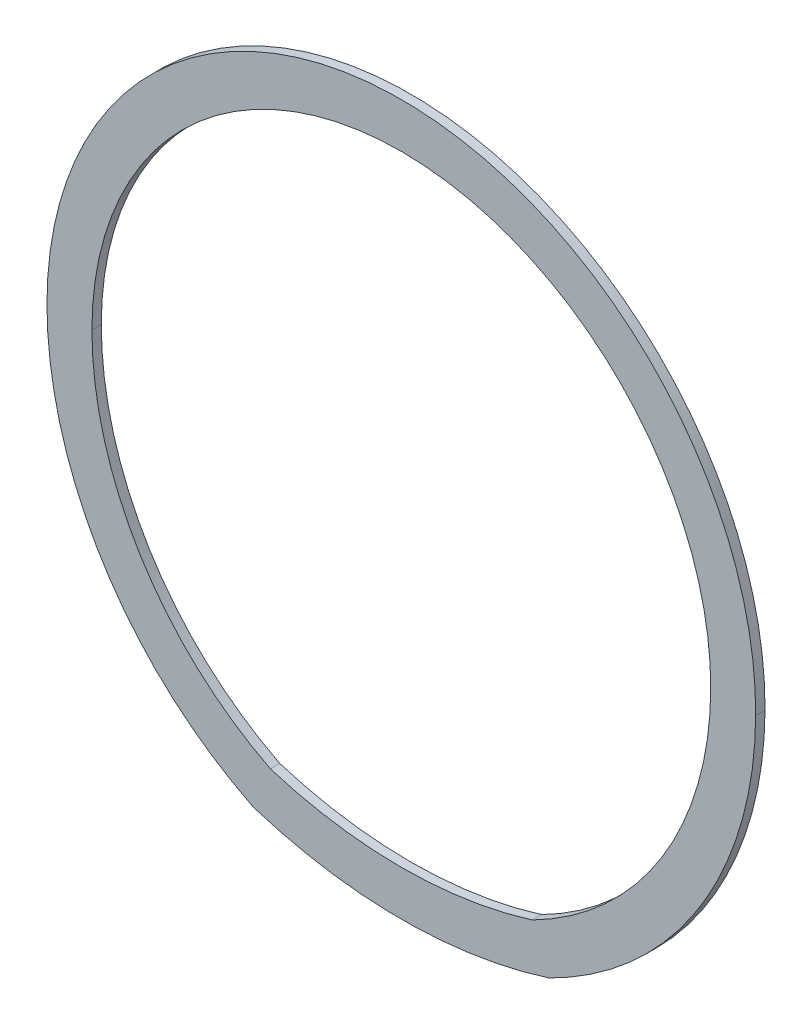
SolidWorks part; units mm, degrees
material "Balsa"
ref_plane "Front Plane" through (0, 0, 0) normal (0, 0, 1) x (1, 0, 0)
ref_plane "Top Plane" through (0, 0, 0) normal (0, 1, 0) x (1, 0, 0)
ref_plane "Right Plane" through (0, 0, 0) normal (1, 0, 0) x (0, 0, -1)
sketch "Sketch2" plane through (0, 0, 0) normal (0, 0, 1) x (1, 0, 0)
  line L0 (0, 0) -> (0.688, 245.4392) construction
  line L1 (-0.1309, -46.7153) -> (-0.2841, -101.3462) construction
  line L2 (0.0534, 19.05) -> (-169.3081, 19.05) construction
  line L3 (-72.7218, -93.726) -> (74.7111, -93.726) construction
  arc A1 (-120.0989, 19.05) -> (120.2036, 18.3433) centre (0.0534, 19.05) cw
  arc A2 (-120.0989, 19.05) -> (-50.0584, -93.726) centre (5.7147, 19.05) ccw
  arc A3 (-50.0584, -93.726) -> (50.1388, -93.726) centre (0.0402, 63.5) ccw
  arc A4 (120.2036, 18.3433) -> (50.1388, -93.726) centre (-5.6406, 19.0835) cw
  arc A5 (-104.8589, 19.05) -> (104.9639, 18.4329) centre (0.0534, 19.05) cw
  arc A6 (104.9639, 18.4329) -> (44.4049, -79.5534) centre (-5.6406, 19.0835) cw
  arc A7 (-44.324, -79.5535) -> (44.4049, -79.5534) centre (0.0402, 63.5) ccw
  arc A8 (-104.8589, 19.05) -> (-44.324, -79.5535) centre (5.7147, 19.05) ccw
  spline S0 degree 3 poles (-3556.5504, 3316.495) (-890.4622, 299.1391) (-150.9999, -230.0461) (69.4764, -82.4823) (75.8596, -77.7331) (81.7614, -72.3621) (85.2966, -68.8071) (85.996, -68.0862) (87.3792, -66.6243) (88.0639, -65.8824) (90.0847, -63.6371) (91.3894, -62.1126) (95.1787, -57.4581) (97.5389, -54.2471) (101.9343, -47.6137) (103.9694, -44.1914) (106.7765, -38.8981) (107.6712, -37.107) (109.3772, -33.4707) (110.1904, -31.6207) (112.481, -26.0415) (113.8153, -22.2742) (116.1105, -14.6467) (117.0712, -10.7866) (118.62, -2.9737) (119.208, 0.9791) (119.8028, 6.9796) (119.953, 8.9949) (120.1541, 13.0067) (120.2055, 15.0081) (120.2151, 20.9991) (119.8425, 28.9519) (118.7088, 36.835) (117.5685, 42.7208) (117.1399, 44.6783) (116.1841, 48.5842) (115.6559, 50.5346) (113.94, 56.3082) (112.6165, 60.0751) (109.6192, 67.4485) (107.9453, 71.055) (104.2453, 78.1066) (102.2192, 81.5518) (99.4588, 85.754) (98.8945, 86.5903) (97.7468, 88.2466) (97.1639, 89.0659) (95.3883, 91.4977) (94.1686, 93.0841) (90.4034, 97.7402) (87.752, 100.7072) (82.1689, 106.369) (79.2371, 109.0639) (74.6247, 112.8977) (73.0514, 114.1408) (70.6363, 115.9521) (69.821, 116.5478) (68.1799, 117.7153) (67.3537, 118.2875) (63.1947, 121.0918) (59.7778, 123.1535) (52.769, 126.9212) (49.1769, 128.6272) (41.816, 131.6806) (38.0473, 133.028) (33.2217, 134.4796) (32.2518, 134.758) (30.3116, 135.2882) (29.34, 135.5404) (26.4206, 136.2591) (24.4685, 136.6873) (18.5945, 137.8219) (14.6552, 138.3782) (6.7301, 139.0933) (2.7444, 139.252) (-2.2675, 139.1959) (-3.2714, 139.172) (-5.2821, 139.0983) (-6.2905, 139.0484) (-9.3072, 138.8606) (-11.3068, 138.6846) (-17.272, 138.0072) (-25.1357, 136.7069) (-32.823, 134.6274) (-38.5216, 132.7724) (-40.41, 132.1048) (-44.1641, 130.6694) (-46.0326, 129.9002) (-376.7108, -16.1688) (6.2798, -1620.0108) (1107.1675, -4694.8808) knots -2.017004 -2.017004 -2.017004 -2.017004 0.03125 0.03125 0.0625 0.09375 0.09375 0.101563 0.101563 0.109375 0.109375 0.125 0.125 0.15625 0.15625 0.1875 0.1875 0.203125 0.203125 0.21875 0.21875 0.25 0.25 0.28125 0.28125 0.3125 0.3125 0.328125 0.328125 0.34375 0.34375 0.375 0.40625 0.40625 0.421875 0.421875 0.4375 0.4375 0.46875 0.46875 0.5 0.5 0.53125 0.53125 0.539063 0.539063 0.546875 0.546875 0.5625 0.5625 0.59375 0.59375 0.625 0.625 0.640625 0.640625 0.648438 0.648438 0.65625 0.65625 0.6875 0.6875 0.71875 0.71875 0.75 0.75 0.757813 0.757813 0.765625 0.765625 0.78125 0.78125 0.8125 0.8125 0.84375 0.84375 0.851563 0.851563 0.859375 0.859375 0.875 0.875 0.90625 0.9375 0.9375 0.953125 0.953125 0.96875 0.96875 3.756216 3.756216 3.756216 3.756216 only from (55.8537, -90.8749) to (-58.6671, 123.6507)
  spline S1 degree 3 poles (55.8537, -90.8749) (59.4151, -88.9779) (62.8499, -86.9173) (69.4764, -82.4823) (75.8596, -77.7331) (81.7614, -72.3621) (85.2966, -68.8071) (85.996, -68.0862) (87.3792, -66.6243) (88.0639, -65.8824) (90.0847, -63.6371) (91.3894, -62.1126) (95.1787, -57.4581) (97.5389, -54.2471) (101.9343, -47.6137) (103.9694, -44.1914) (106.7765, -38.8981) (107.6712, -37.107) (109.3772, -33.4707) (110.1904, -31.6207) (112.481, -26.0415) (113.8153, -22.2742) (116.1105, -14.6467) (117.0712, -10.7866) (118.62, -2.9737) (119.208, 0.9791) (119.8028, 6.9796) (119.953, 8.9949) (120.1541, 13.0067) (120.2055, 15.0081) (120.2151, 20.9991) (119.8425, 28.9519) (118.7088, 36.835) (117.5685, 42.7208) (117.1399, 44.6783) (116.1841, 48.5842) (115.6559, 50.5346) (113.94, 56.3082) (112.6165, 60.0751) (109.6192, 67.4485) (107.9453, 71.055) (104.2453, 78.1066) (102.2192, 81.5518) (99.4588, 85.754) (98.8945, 86.5903) (97.7468, 88.2466) (97.1639, 89.0659) (95.3883, 91.4977) (94.1686, 93.0841) (90.4034, 97.7402) (87.752, 100.7072) (82.1689, 106.369) (79.2371, 109.0639) (74.6247, 112.8977) (73.0514, 114.1408) (70.6363, 115.9521) (69.821, 116.5478) (68.1799, 117.7153) (67.3537, 118.2875) (63.1947, 121.0918) (59.7778, 123.1535) (52.769, 126.9212) (49.1769, 128.6272) (41.816, 131.6806) (38.0473, 133.028) (33.2217, 134.4796) (32.2518, 134.758) (30.3116, 135.2882) (29.34, 135.5404) (26.4206, 136.2591) (24.4685, 136.6873) (18.5945, 137.8219) (14.6552, 138.3782) (6.7301, 139.0933) (2.7444, 139.252) (-2.2675, 139.1959) (-3.2714, 139.172) (-5.2821, 139.0983) (-6.2905, 139.0484) (-9.3072, 138.8606) (-11.3068, 138.6846) (-17.272, 138.0072) (-25.1357, 136.7069) (-32.823, 134.6274) (-38.5216, 132.7724) (-40.41, 132.1048) (-44.1641, 130.6694) (-46.0326, 129.9002) (-51.5624, 127.4576) (-55.1595, 125.6458) (-58.6671, 123.6507) knots 0 0 0 0 0.03125 0.03125 0.0625 0.09375 0.09375 0.101563 0.101563 0.109375 0.109375 0.125 0.125 0.15625 0.15625 0.1875 0.1875 0.203125 0.203125 0.21875 0.21875 0.25 0.25 0.28125 0.28125 0.3125 0.3125 0.328125 0.328125 0.34375 0.34375 0.375 0.40625 0.40625 0.421875 0.421875 0.4375 0.4375 0.46875 0.46875 0.5 0.5 0.53125 0.53125 0.539063 0.539063 0.546875 0.546875 0.5625 0.5625 0.59375 0.59375 0.625 0.625 0.640625 0.640625 0.648438 0.648438 0.65625 0.65625 0.6875 0.6875 0.71875 0.71875 0.75 0.75 0.757813 0.757813 0.765625 0.765625 0.78125 0.78125 0.8125 0.8125 0.84375 0.84375 0.851563 0.851563 0.859375 0.859375 0.875 0.875 0.90625 0.9375 0.9375 0.953125 0.953125 0.96875 0.96875 1 1 1 1 construction
  spline S2 degree 3 poles (3662.2203, -3163.4678) (929.3471, -255.8994) (141.4488, 279.257) (-76.9523, 111.0297) (-81.0984, 107.3558) (-85.9766, 102.3921) (-86.9369, 101.3807) (-88.8267, 99.3202) (-89.7577, 98.2691) (-92.4915, 95.0728) (-94.2304, 92.8907) (-99.2026, 86.1952) (-102.1931, 81.5333) (-106.1993, 74.2476) (-107.4545, 71.77) (-109.2154, 67.9791) (-109.782, 66.7031) (-110.874, 64.1258) (-111.4002, 62.8224) (-113.9097, 56.2871) (-115.5417, 50.9767) (-118.0823, 40.1978) (-118.9908, 34.7292) (-119.6657, 27.7928) (-119.7775, 26.4005) (-119.9543, 23.6055) (-120.0192, 22.2016) (-120.1418, 18.0057) (-120.1286, 15.2199) (-119.8102, 6.8959) (-119.2278, 1.3912) (-117.8014, -6.7994) (-117.2335, -9.5184) (-116.2404, -13.58) (-115.8858, -14.9311) (-115.1288, -17.6274) (-114.7258, -18.9739) (-112.6063, -25.6411) (-108.5276, -35.9696) (-103.1136, -45.6397) (-99.3011, -51.4722) (-98.5171, -52.628) (-96.9053, -54.9182) (-96.0765, -56.0537) (-93.5433, -59.4015) (-91.7865, -61.5635) (-86.3167, -67.8444) (-82.4051, -71.759) (-76.1398, -77.2217) (-73.9848, -78.9742) (-70.6503, -81.498) (-69.5218, -82.3217) (-67.2303, -83.9337) (-66.0665, -84.7222) (469.7497, -434.2328) (3136.6288, 3880.8147) (1236.3427, -1793.8053) knots -2.986162 -2.986162 -2.986162 -2.986162 0.0625 0.0625 0.125 0.125 0.140625 0.140625 0.15625 0.15625 0.1875 0.1875 0.25 0.25 0.28125 0.28125 0.296875 0.296875 0.3125 0.3125 0.375 0.375 0.4375 0.4375 0.453125 0.453125 0.46875 0.46875 0.5 0.5 0.5625 0.5625 0.59375 0.59375 0.609375 0.609375 0.625 0.625 0.6875 0.75 0.75 0.765625 0.765625 0.78125 0.78125 0.8125 0.8125 0.875 0.875 0.90625 0.90625 0.921875 0.921875 0.9375 0.9375 8.066371 8.066371 8.066371 8.066371 only from (-58.6671, 123.6507) to (-50.3455, -93.5936)
  spline S3 degree 3 poles (-3018.0483, 3798.4999) (596.0577, -1965.6007) (966.7905, -1089.5518) (-1079.2067, 4734.2621) knots -155.5553 -155.5553 -155.5553 -155.5553 163.906166 163.906166 163.906166 163.906166 only from (49.819, -93.8744) to (55.8537, -90.8749)
  spline S4 degree 3 poles (49.819, -93.8744) (51.8584, -92.9316) (53.87, -91.9317) (55.8537, -90.8749) knots 0 0 0 0 1 1 1 1 construction
  spline S5 degree 3 poles (-58.6671, 123.6507) (-63.5487, 120.874) (-68.1774, 117.7887) (-76.9523, 111.0297) (-81.0984, 107.3558) (-85.9766, 102.3921) (-86.9369, 101.3807) (-88.8267, 99.3202) (-89.7577, 98.2691) (-92.4915, 95.0728) (-94.2304, 92.8907) (-99.2026, 86.1952) (-102.1931, 81.5333) (-106.1993, 74.2476) (-107.4545, 71.77) (-109.2154, 67.9791) (-109.782, 66.7031) (-110.874, 64.1258) (-111.4002, 62.8224) (-113.9097, 56.2871) (-115.5417, 50.9767) (-118.0823, 40.1978) (-118.9908, 34.7292) (-119.6657, 27.7928) (-119.7775, 26.4005) (-119.9543, 23.6055) (-120.0192, 22.2016) (-120.1418, 18.0057) (-120.1286, 15.2199) (-119.8102, 6.8959) (-119.2278, 1.3912) (-117.8014, -6.7994) (-117.2335, -9.5184) (-116.2404, -13.58) (-115.8858, -14.9311) (-115.1288, -17.6274) (-114.7258, -18.9739) (-112.6063, -25.6411) (-108.5276, -35.9696) (-103.1136, -45.6397) (-99.3011, -51.4722) (-98.5171, -52.628) (-96.9053, -54.9182) (-96.0765, -56.0537) (-93.5433, -59.4015) (-91.7865, -61.5635) (-86.3167, -67.8444) (-82.4051, -71.759) (-76.1398, -77.2217) (-73.9848, -78.9742) (-70.6503, -81.498) (-69.5218, -82.3217) (-67.2303, -83.9337) (-66.0665, -84.7222) (-60.2073, -88.5441) (-55.3561, -91.2432) (-50.3455, -93.5936) knots 0 0 0 0 0.0625 0.0625 0.125 0.125 0.140625 0.140625 0.15625 0.15625 0.1875 0.1875 0.25 0.25 0.28125 0.28125 0.296875 0.296875 0.3125 0.3125 0.375 0.375 0.4375 0.4375 0.453125 0.453125 0.46875 0.46875 0.5 0.5 0.5625 0.5625 0.59375 0.59375 0.609375 0.609375 0.625 0.625 0.6875 0.75 0.75 0.765625 0.765625 0.78125 0.78125 0.8125 0.8125 0.875 0.875 0.90625 0.90625 0.921875 0.921875 0.9375 0.9375 1 1 1 1 construction
  spline S6 degree 3 poles (-1041.2319, 4783.2262) (121.3563, 33.3828) (96.3248, -78.5551) (45.8458, -95.3665) (44.8322, -95.6594) (41.7708, -96.4587) (39.7032, -96.8873) (35.5384, -97.6293) (33.4392, -97.9405) (29.2422, -98.4783) (27.1412, -98.7049) (20.8322, -99.2882) (16.6185, -99.55) (8.1799, -99.8877) (3.9548, -99.9623) (-4.5058, -99.9387) (-8.734, -99.8405) (-17.1695, -99.4557) (-21.3793, -99.1705) (-27.6778, -98.553) (-29.7745, -98.3152) (-33.9608, -97.7556) (-36.0504, -97.4344) (-39.177, -96.8603) (-40.2191, -96.653) (-42.292, -96.1992) (-43.3225, -95.953) (-45.3676, -95.407) (-46.3821, -95.1076) (-97.2327, -77.8515) (-118.0583, 35.3638) (1242.9953, 4733.742) knots -1.510039 -1.510039 -1.510039 -1.510039 0.03125 0.03125 0.0625 0.0625 0.125 0.125 0.1875 0.1875 0.25 0.25 0.375 0.375 0.5 0.5 0.625 0.625 0.75 0.75 0.8125 0.8125 0.875 0.875 0.90625 0.90625 0.9375 0.9375 0.96875 0.96875 2.52296 2.52296 2.52296 2.52296 only from (49.8185, -93.8746) to (-50.3451, -93.5938)
  spline S7 degree 3 poles (49.8185, -93.8746) (48.8452, -94.325) (47.8521, -94.6984) (45.8458, -95.3665) (44.8322, -95.6594) (41.7708, -96.4587) (39.7032, -96.8873) (35.5384, -97.6293) (33.4392, -97.9405) (29.2422, -98.4783) (27.1412, -98.7049) (20.8322, -99.2882) (16.6185, -99.55) (8.1799, -99.8877) (3.9548, -99.9623) (-4.5058, -99.9387) (-8.734, -99.8405) (-17.1695, -99.4557) (-21.3793, -99.1705) (-27.6778, -98.553) (-29.7745, -98.3152) (-33.9608, -97.7556) (-36.0504, -97.4344) (-39.177, -96.8603) (-40.2191, -96.653) (-42.292, -96.1992) (-43.3225, -95.953) (-45.3676, -95.407) (-46.3821, -95.1076) (-48.3867, -94.4274) (-49.3773, -94.0483) (-50.3451, -93.5938) knots 0 0 0 0 0.03125 0.03125 0.0625 0.0625 0.125 0.125 0.1875 0.1875 0.25 0.25 0.375 0.375 0.5 0.5 0.625 0.625 0.75 0.75 0.8125 0.8125 0.875 0.875 0.90625 0.90625 0.9375 0.9375 0.96875 0.96875 1 1 1 1 construction
  spline S8 degree 1 poles (44.4895, -82.3468) (49.8828, -79.6661) knots 0 0 1 1 construction
  spline S9 degree 1 poles (49.8828, -79.6661) (-52.388, 112.6115) knots 0 0 1 1 construction
  spline S10 degree 1 poles (-52.388, 112.6115) (-44.952, -82.0958) knots 0 0 1 1 construction
  spline S11 degree 3 poles (44.4895, -82.3468) (44.9451, -82.1361) (45.8533, -81.7084) (47.2062, -81.0479) (48.5497, -80.3682) (49.4396, -79.9022) (49.8828, -79.6661) knots 0 0 0 0 0.250007 0.500014 0.750021 1.000028 1.000028 1.000028 1.000028 construction
  spline S12 degree 3 poles (49.8828, -79.6661) (51.4682, -78.8216) (54.6039, -77.0481) (60.6329, -73.2256) (67.7713, -67.9145) (75.6946, -60.7068) (85.376, -49.946) (92.2499, -39.5527) (97.0635, -29.9209) (99.9774, -23.2906) (102.9687, -14.8438) (105.5551, -4.452) (106.8747, 4.4138) (107.4138, 11.642) (107.598, 18.8242) (107.1791, 27.7507) (105.6575, 38.3493) (103.0737, 48.9109) (99.5091, 59.0529) (95.0071, 68.7524) (90.4672, 76.4728) (86.3465, 82.4205) (79.7918, 90.9419) (71.0678, 99.805) (59.5047, 108.4813) (50.3361, 114.0108) (40.7123, 118.5824) (32.2831, 121.5955) (25.3334, 123.4944) (18.366, 125.0225) (9.571, 126.2643) (-1.0997, 126.6912) (-11.9104, 126.0185) (-22.4327, 124.2743) (-36.1547, 120.5693) (-46.1487, 116.1604) (-52.388, 112.6115) knots 0 0 0 0 0.015625 0.03125 0.0625 0.09375 0.125 0.1875 0.203125 0.21875 0.25 0.28125 0.3125 0.328125 0.34375 0.375 0.40625 0.4375 0.46875 0.5 0.53125 0.546875 0.5625 0.625 0.65625 0.6875 0.71875 0.75 0.765625 0.78125 0.8125 0.84375 0.875 0.90625 0.9375 1 1 1 1 construction
  spline S13 degree 3 poles (-52.388, 112.6115) (-54.5585, 111.3769) (-58.8261, 108.7475) (-66.8816, 102.9693) (-76.1597, 94.757) (-85.9932, 83.258) (-92.681, 72.8203) (-97.1816, 63.9424) (-101.112, 54.6656) (-104.776, 42.7383) (-106.8137, 30.488) (-107.4512, 20.4245) (-107.4028, 10.4189) (-106.3564, 0.5368) (-104.3212, -9.2152) (-101.5955, -18.9231) (-97.0158, -30.5128) (-90.9605, -41.334) (-85.1677, -49.567) (-78.8706, -57.3154) (-71.8665, -64.3232) (-64.1621, -70.5906) (-57.9948, -74.9291) (-51.5954, -78.7902) (-47.193, -81.0446) (-44.952, -82.0958) knots 0 0 0 0 0.03125 0.0625 0.125 0.1875 0.25 0.28125 0.3125 0.375 0.4375 0.46875 0.5 0.5625 0.59375 0.625 0.6875 0.75 0.78125 0.8125 0.875 0.90625 0.9375 0.96875 1 1 1 1 construction
  spline S14 degree 1 poles (44.4849, -82.3489) (-44.9469, -82.0982) knots 0 0 1 1 construction
  spline S15 degree 3 poles (44.4849, -82.3489) (44.3746, -82.3999) (44.1627, -82.4934) (43.6492, -82.7012) (42.8561, -82.9839) (41.7841, -83.3184) (40.2245, -83.7477) (38.1103, -84.2445) (35.4106, -84.7656) (32.6063, -85.224) (28.7759, -85.7537) (23.885, -86.2821) (17.9201, -86.7432) (11.8971, -87.0512) (5.8396, -87.2261) (-2.2666, -87.2864) (-10.3738, -87.0974) (-18.3985, -86.6419) (-24.3556, -86.1481) (-29.2377, -85.5934) (-33.056, -85.0443) (-35.8555, -84.5718) (-38.5671, -84.0318) (-40.6899, -83.5223) (-42.2517, -83.0828) (-43.3238, -82.7417) (-44.1147, -82.4546) (-44.6269, -82.2439) (-44.8373, -82.1497) (-44.9469, -82.0982) knots 0 0 0 0 0.007812 0.015625 0.03125 0.046875 0.0625 0.09375 0.125 0.15625 0.1875 0.25 0.3125 0.375 0.4375 0.5 0.625 0.6875 0.75 0.8125 0.84375 0.875 0.90625 0.9375 0.953125 0.96875 0.984375 0.992188 1 1 1 1 construction
  point P12 (-0.2802, -99.9505)
  dimension "D3" = 19.05
  dimension "D4" = 93.726
  dimension "D5" = 63.5
  dimension "D6" = 15.24
  dimension "D1" = 12.7
  dimension "D2" = 12.7
extrude "Boss-Extrude1" add sketch "Sketch2" along normal mid plane 3.175
